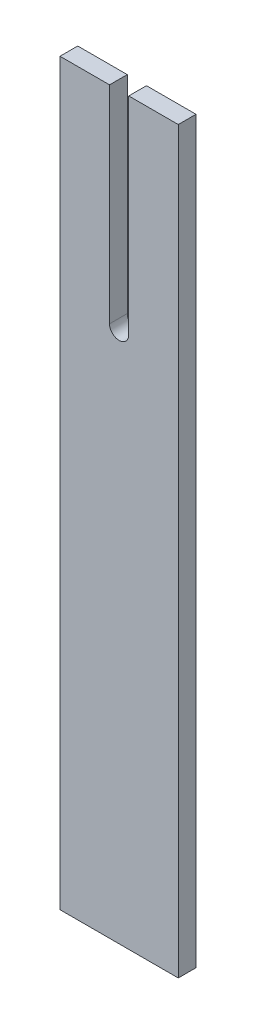
SolidWorks part; units mm, degrees
material "Acrylic (Medium-high impact)"
ref_plane "Front Plane" through (0, 0, 0) normal (0, 0, 1) x (1, 0, 0)
ref_plane "Top Plane" through (0, 0, 0) normal (0, 1, 0) x (1, 0, 0)
ref_plane "Right Plane" through (0, 0, 0) normal (1, 0, 0) x (0, 0, -1)
sketch "Sketch1" plane through (0, 0, 0) normal (0, 0, 1) x (1, 0, 0)
  line L1 (-20, -125) -> (20, -125)
  line L2 (-20, -125) -> (-20, 125)
  line L3 (-20, 125) -> (20, 125)
  line L4 (20, -125) -> (20, 125)
  line L5 (-20, -125) -> (20, 125) construction
  line L6 (-20, 125) -> (20, -125) construction
  point P0 (0, 0)
  dimension "D1" = 40
  dimension "D2" = 250
extrude "Boss-Extrude1" add sketch "Sketch1" along normal blind 6
sketch "Sketch2" plane through (0, 0, 6) normal (0, 0, 1) x (1, 0, 0)
  line L3 (-3.25, 125) -> (3.25, 125)
  line L4 (20, 125) -> (-20, 125) construction
  line L5 (-3.25, 125) -> (-3.25, 55)
  line L6 (3.25, 125) -> (3.25, 55)
  arc A0 (3.25, 55) -> (-3.25, 55) centre (0, 55) cw
  point P5 (0, 125)
  point P9 (0, 0)
  dimension "D1" = 70
extrude "Cut-Extrude1" cut sketch "Sketch2" against normal blind 6
